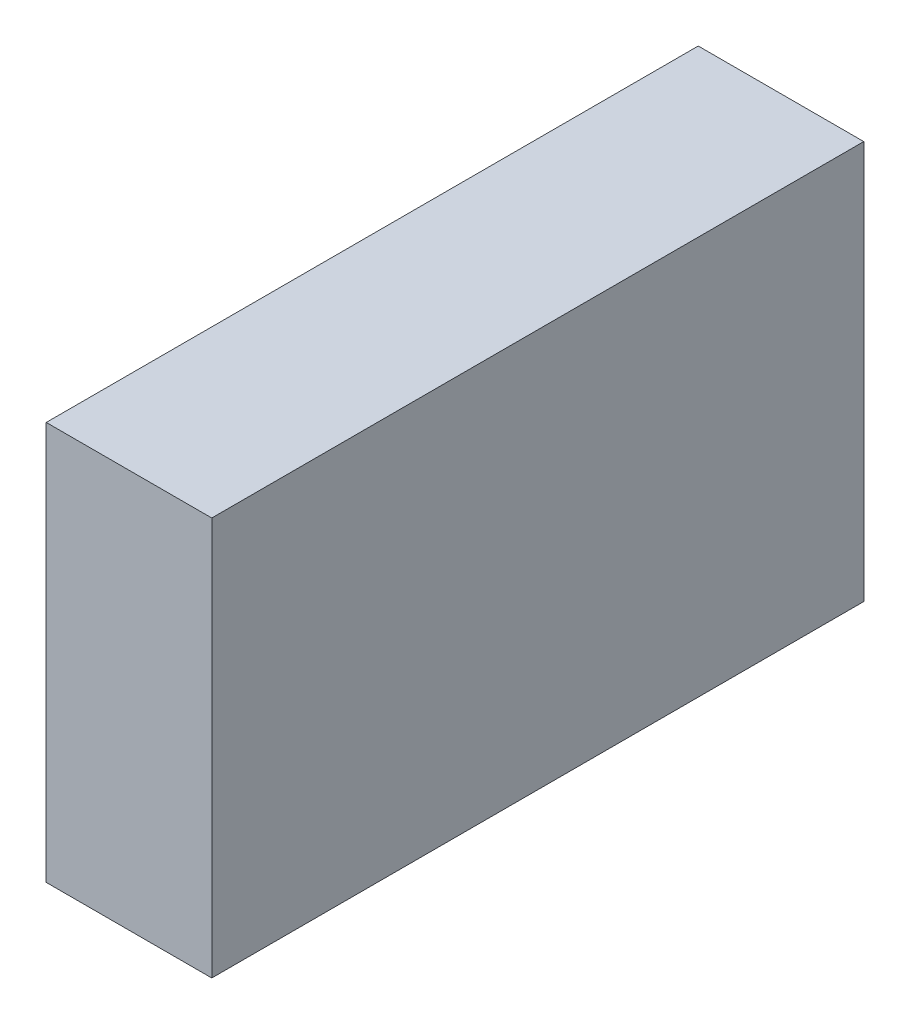
SolidWorks part; units mm, degrees
ref_plane "FP" through (0, 0, 0) normal (0, 0, 1) x (1, 0, 0)
ref_plane "TP" through (0, 0, 0) normal (0, 1, 0) x (1, 0, 0)
ref_plane "RP" through (0, 0, 0) normal (1, 0, 0) x (0, 0, -1)
sketch "Sketch1" plane through (0, 0, 0) normal (0, 0, 1) x (1, 0, 0)
  line L9 (70.44, -29.94) -> (70.44, 29.94)
  line L10 (45.56, -29.94) -> (70.44, -29.94)
  line L11 (45.56, 29.94) -> (45.56, -29.94)
  line L12 (70.44, 29.94) -> (45.56, 29.94)
  line L13 (70.44, -29.94) -> (70.44, 29.94)
  line L14 (45.56, -29.94) -> (70.44, -29.94)
  line L15 (45.56, 29.94) -> (45.56, -29.94)
  line L16 (70.44, 29.94) -> (45.56, 29.94)
  dimension "D1" = 0.06
extrude "Boss-Extrude1" add sketch "Sketch1" against normal blind 98
